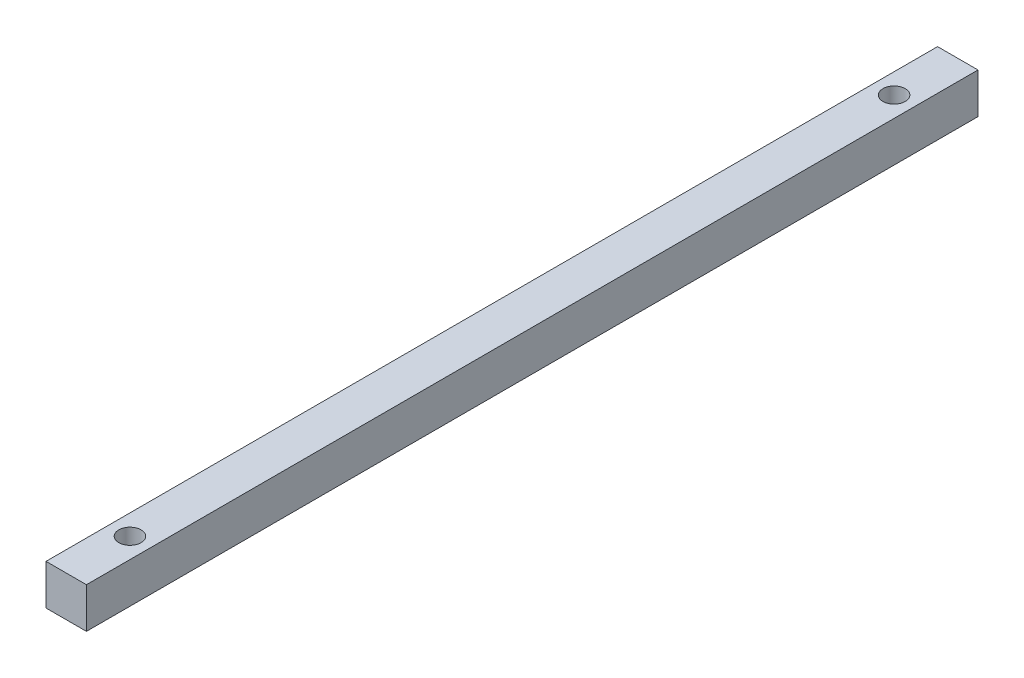
SolidWorks part; units mm, degrees
ref_plane "Front Plane" through (0, 0, 0) normal (0, 0, 1) x (1, 0, 0)
ref_plane "Top Plane" through (0, 0, 0) normal (0, 1, 0) x (1, 0, 0)
ref_plane "Right Plane" through (0, 0, 0) normal (1, 0, 0) x (0, 0, -1)
sketch "Sketch1" plane through (0, 0, 0) normal (0, 0, 1) x (1, 0, 0)
  line L0 (-3.175, 3.175) -> (-3.175, -3.175) construction
  line L1 (-3.175, 3.175) -> (3.175, 3.175) construction
  line L2 (-3.175, 0) -> (0, 0) construction
  line L3 (0, 0) -> (0, 3.175) construction
  dimension "Thickness" = 6.35
  dimension "Width" = 6.35
ref_plane "Plane1" through (-3.175, 3.175, 0) normal (0, -1, 0) x (-1, 0, 0)
sketch "Sketch2" plane through (-3.175, 3.175, 0) normal (0, 1, 0) x (1, 0, 0)
  line L0 (3.175, -609.6) -> (3.175, 609.6) construction
  point P2 (3.175, -596.9)
  point P3 (3.175, 596.9)
  dimension "Length" = 1219.2
  dimension "D1" = 12.7
  dimension "D2" = 12.7
sketch "Sketch3" plane through (0, 0, 0) normal (0, 0, 1) x (1, 0, 0)
  line L1 (-3.175, -3.175) -> (3.175, -3.175)
  line L2 (-3.175, -3.175) -> (-3.175, 3.175)
  line L3 (-3.175, 3.175) -> (3.175, 3.175)
  line L4 (3.175, -3.175) -> (3.175, 3.175)
  line L5 (0, 3.175) -> (0, -3.175) construction
  line L6 (-3.175, 0) -> (3.175, 0) construction
  line L7 (-3.175, 0) -> (0, 0) construction
extrude "Boss-Extrude1" add sketch "Sketch3" along normal up to vertex (609.6 mm away) and the other way up to vertex (609.6 mm away) up to point (0, 3.175, 609.6) other way up to point (0, 3.175, -609.6)
ref_plane "Plane2" through (0, 0, -469.6) normal (0, 0, -1) x (-1, 0, 0)
sketch "Sketch4" plane through (0, 0, -469.6) normal (0, 0, -1) x (-1, 0, 0)
  line L0 (-3.175, -3.175) -> (-3.175, 3.175) construction
  line L1 (-3.675, 3.675) -> (3.675, 3.675)
  line L2 (-3.675, 3.675) -> (-3.675, -3.675)
  line L3 (-3.675, -3.675) -> (3.675, -3.675)
  line L4 (3.675, 3.675) -> (3.675, -3.675)
  line L5 (-3.675, 3.675) -> (3.675, -3.675) construction
  line L6 (-3.675, -3.675) -> (3.675, 3.675) construction
  point P0 (0, 0)
  dimension "D1" = 0.5
extrude "Cut-Extrude1" cut sketch "Sketch4" against normal through all
sketch "Sketch5" plane through (0, 3.175, 0) normal (0, 1, 0) x (1, 0, 0)
  line L0 (3.175, 609.6) -> (-3.175, 609.6) construction
  line L1 (-3.175, 469.6) -> (3.175, 469.6) construction
  line L2 (3.175, 469.6) -> (3.175, 609.6) construction
  circle A0 centre (0, 599.6) radius 1.75
  circle A1 centre (0, 479.6) radius 1.75
  dimension "D2" = 3.5
  dimension "D1" = 10
  dimension "D3" = 10
  dimension "D4" = 3.175
extrude "Cut-Extrude2" cut sketch "Sketch5" against normal through all
equation "\"D1@Sketch2\"=\"Width@Sketch1\"*2"
equation "\"D2@Sketch2\"=\"D1@Sketch2\""
